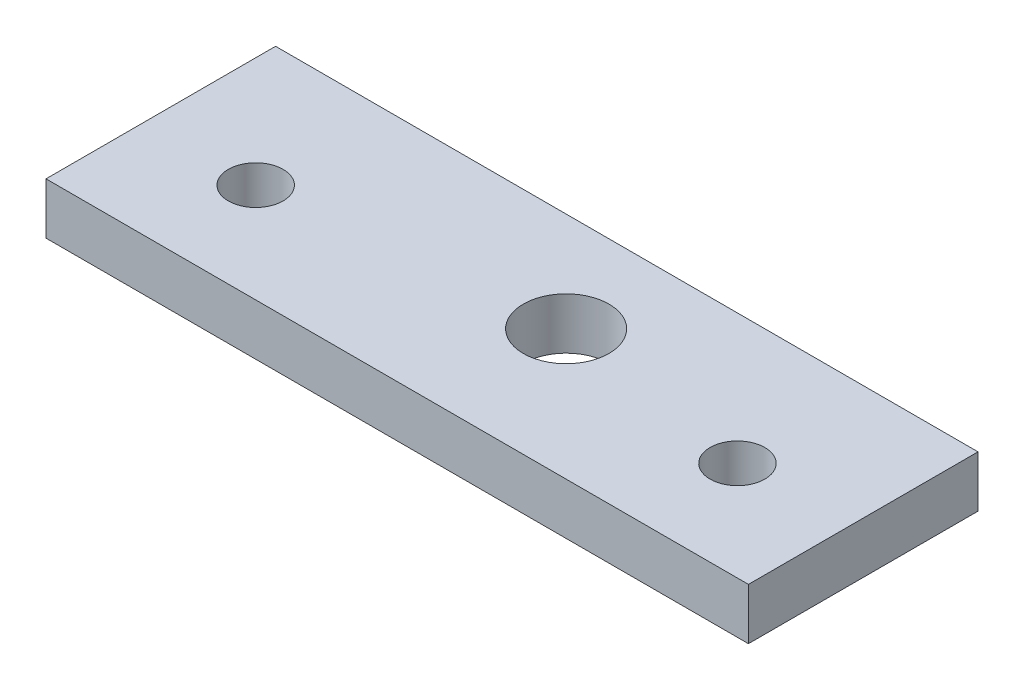
SolidWorks part; units mm, degrees
ref_plane "Front Plane" through (0, 0, 0) normal (0, 0, 1) x (1, 0, 0)
ref_plane "Top Plane" through (0, 0, 0) normal (0, 1, 0) x (1, 0, 0)
ref_plane "Right Plane" through (0, 0, 0) normal (1, 0, 0) x (0, 0, -1)
sketch "Sketch1" plane through (0, 0, 0) normal (0, 1, 0) x (1, 0, 0)
  line L0 (-9.5212, -2.0476) -> (10.9788, -2.0476)
  line L1 (-9.5212, -2.0476) -> (-9.5212, 4.6524)
  line L2 (-9.5212, 4.6524) -> (10.9788, 4.6524)
  line L3 (10.9788, -2.0476) -> (10.9788, 4.6524)
  circle A0 centre (-6.3012, 0.8524) radius 0.8
  circle A1 centre (1.8588, 1.7524) radius 1.25
  circle A2 centre (7.7588, 0.8524) radius 0.8
  point P10 (0, 0)
extrude "Boss-Extrude1" add sketch "Sketch1" along normal blind 1.5
